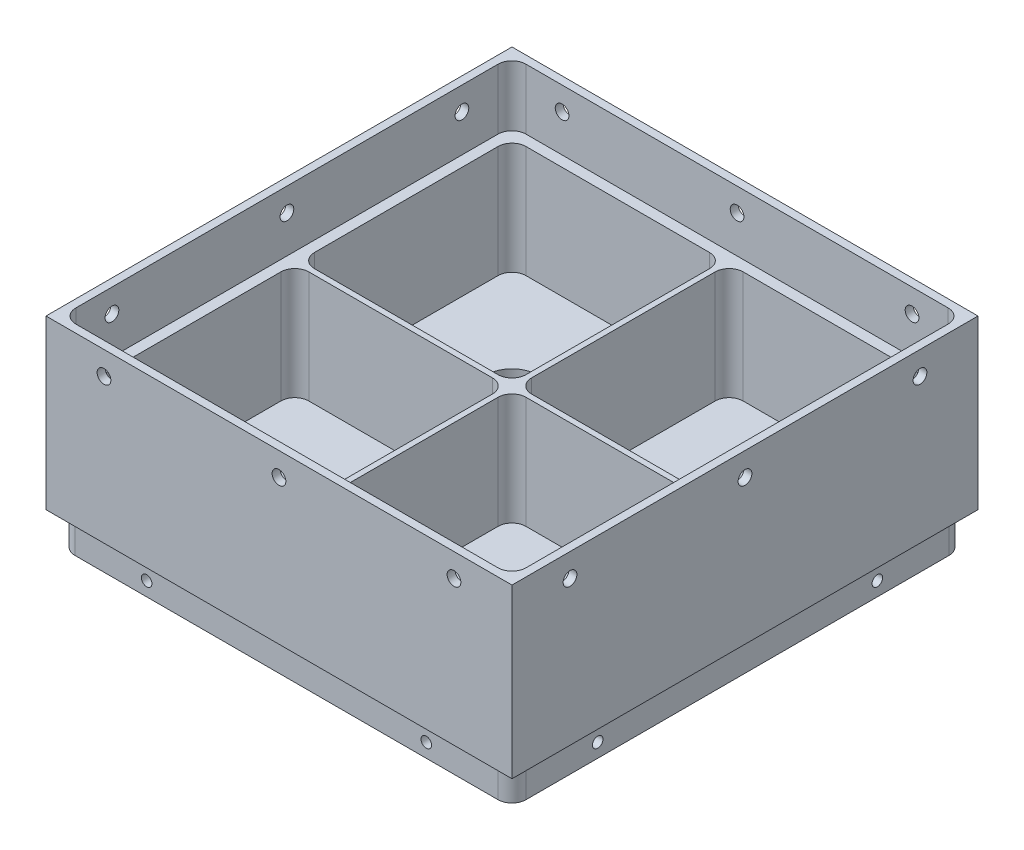
SolidWorks part; units mm, degrees
material "6061-T6 (SS)"
ref_plane "Front Plane" through (0, 0, 0) normal (0, 0, 1) x (1, 0, 0)
ref_plane "Top Plane" through (0, 0, 0) normal (0, 1, 0) x (1, 0, 0)
ref_plane "Right Plane" through (0, 0, 0) normal (1, 0, 0) x (0, 0, -1)
sketch "Sketch1" plane through (0, 0, 0) normal (0, 1, 0) x (1, 0, 0)
  line L0 (0, -50) -> (0, 50) construction
  line L1 (-50, -50) -> (50, -50)
  line L2 (-50, -50) -> (-50, 50)
  line L3 (-50, 50) -> (50, 50)
  line L4 (50, -50) -> (50, 50)
  line L5 (-50, -50) -> (50, 50) construction
  line L6 (-50, 50) -> (50, -50) construction
  line L7 (-50, 0) -> (50, 0) construction
  line L8 (-46, -46) -> (-46, -0.6)
  line L9 (-46, 46) -> (-0.6, 46)
  line L10 (46, -46) -> (46, -0.6)
  line L11 (-46, -46) -> (-0.6, -46)
  line L12 (0.6, -0.6) -> (0.6, 0.6) construction
  line L13 (-46, -0.6) -> (46, -0.6) construction
  line L14 (-0.6, -0.6) -> (-0.6, 0.6) construction
  line L15 (-46, 0.6) -> (46, 0.6) construction
  line L16 (0.6, 46) -> (46, 46)
  line L17 (-0.6, -50) -> (-0.6, 50) construction
  line L18 (0.6, -50) -> (0.6, 50) construction
  line L19 (-46, 0.6) -> (-46, 46)
  line L20 (-46, 46) -> (46, 46) construction
  line L21 (-50, -0.6) -> (50, -0.6) construction
  line L22 (0.6, -46) -> (46, -46)
  line L23 (-46, -46) -> (-46, 46) construction
  line L24 (-50, 0.6) -> (50, 0.6) construction
  line L25 (46, 0.6) -> (46, 46)
  line L26 (-46, -46) -> (46, -46) construction
  line L27 (-0.6, 0.6) -> (-0.6, 46)
  line L28 (46, -46) -> (46, 46) construction
  line L29 (-0.6, -0.6) -> (-0.6, -46)
  line L30 (0.6, 0.6) -> (0.6, 46)
  line L31 (0.6, -0.6) -> (0.6, -46)
  line L32 (-46, 0.6) -> (-0.6, 0.6)
  line L33 (-46, -0.6) -> (-0.6, -0.6)
  line L34 (0.6, 0.6) -> (46, 0.6)
  line L35 (0.6, -0.6) -> (46, -0.6)
  point P0 (0, 0)
  dimension "D1" = 100
  dimension "D2" = 100
  dimension "D3" = 4
  dimension "D4" = 0.6
  dimension "D5" = 0.6
extrude "Boss-Extrude1" add sketch "Sketch1" along normal blind 24
fillet "Fillet1" radius 3 16 edges at (-46, 12, 46) (0.6, 12, 46) (-0.6, 12, 46) (46, 12, 46) (46, 12, -0.6) (46, 12, -46) (0.6, 12, -46) (-0.6, 12, -46) (-46, 12, -0.6) (-46, 12, -46) (0.6, 12, 0.6) (-0.6, 12, 0.6) (0.6, 12, -0.6) (-0.6, 12, -0.6) (46, 12, 0.6) (-46, 12, 0.6)
sketch "Sketch2" plane through (0, 0, 0) normal (0, -1, 0) x (1, 0, 0)
  line L1 (50, -50) -> (-50, -50)
  line L2 (50, -50) -> (50, 50)
  line L3 (50, 50) -> (-50, 50)
  line L4 (-50, -50) -> (-50, 50)
  line L5 (50, -50) -> (-50, 50) construction
  line L6 (50, 50) -> (-50, -50) construction
  point P0 (0, 0)
  dimension "D1" = 100
extrude "Boss-Extrude2" add sketch "Sketch2" along normal blind 6
sketch "Sketch3" plane through (0, -6, 0) normal (0, -1, 0) x (1, 0, 0)
  line L0 (48.4, -48.4) -> (48.4, 48.4)
  line L1 (50, -50) -> (-50, -50)
  line L2 (50, -50) -> (50, 50)
  line L3 (50, 50) -> (-50, 50)
  line L4 (-50, -50) -> (-50, 50)
  line L5 (50, -50) -> (-50, 50) construction
  line L6 (50, 50) -> (-50, -50) construction
  line L7 (48.4, 48.4) -> (-48.4, 48.4)
  line L8 (-48.4, -48.4) -> (-48.4, 48.4)
  line L9 (48.4, -48.4) -> (-48.4, -48.4)
  point P0 (0, 0)
  dimension "D1" = 1.6
extrude "Cut-Extrude1" cut sketch "Sketch3" against normal blind 7
sketch "Sketch4" plane through (0, -6, 0) normal (0, -1, 0) x (1, 0, 0)
  line L1 (47.945, -45.085) -> (-47.945, -45.085) construction
  line L2 (47.945, -45.085) -> (47.945, 45.085) construction
  line L3 (47.945, 45.085) -> (-47.945, 45.085) construction
  line L4 (-47.945, -45.085) -> (-47.945, 45.085) construction
  line L5 (47.945, -45.085) -> (-47.945, 45.085) construction
  line L6 (47.945, 45.085) -> (-47.945, -45.085) construction
  circle A0 centre (42.865, -40.005) radius 1.1305
  circle A1 centre (-42.865, -37.465) radius 1.1305
  circle A2 centre (42.865, 40.005) radius 1.1305
  circle A3 centre (-42.865, 36.195) radius 1.1305
  point P0 (0, 0)
  dimension "D5" = 2.261
  dimension "D8" = 2.261
  dimension "D11" = 2.261
  dimension "D13" = 2.261
  dimension "D1" = 90.17
  dimension "D2" = 95.89
  dimension "D3" = 5.08
  dimension "D4" = 5.08
  dimension "D6" = 90.81
  dimension "D7" = 7.62
  dimension "D9" = 81.28
  dimension "D10" = 90.81
  dimension "D12" = 5.08
  dimension "D14" = 5.08
extrude "Cut-Extrude2" cut sketch "Sketch4" against normal blind 4.7
sketch "Sketch5" plane through (0, 24, 0) normal (0, 1, 0) x (1, 0, 0)
  line L0 (-48.3, -48.3) -> (-48.3, 48.3)
  line L1 (50, -50) -> (-50, -50)
  line L2 (50, -50) -> (50, 50)
  line L3 (50, 50) -> (-50, 50)
  line L4 (-50, -50) -> (-50, 50)
  line L5 (50, -50) -> (-50, 50) construction
  line L6 (50, 50) -> (-50, -50) construction
  line L7 (48.3, 48.3) -> (-48.3, 48.3)
  line L8 (48.3, -48.3) -> (48.3, 48.3)
  line L9 (48.3, -48.3) -> (-48.3, -48.3)
  point P0 (0, 0)
  dimension "D1" = 1.7
extrude "Boss-Extrude3" add sketch "Sketch5" along normal blind 13
fillet "Fillet2" radius 3 8 edges at (48.3, 30.5, 48.3) (-48.3, 30.5, 48.3) (-48.3, 30.5, -48.3) (48.3, 30.5, -48.3) (-48.4, -2.5, -48.4) (-48.4, -2.5, 48.4) (48.4, -2.5, 48.4) (48.4, -2.5, -48.4)
sketch "Sketch6" plane through (0, 0, 0) normal (0, 1, 0) x (1, 0, 0)
  line L0 (-23.3, 46) -> (-23.3, -46) construction
  line L1 (-3.6, 46) -> (-43, 46) construction
  line L2 (-43, -46) -> (-3.6, -46) construction
  line L3 (23.3, -46) -> (23.3, 46) construction
  line L6 (45.8197, 23.4167) -> (46, 23.3)
  line L7 (3.6, -46) -> (43, -46) construction
  line L8 (43, 46) -> (3.6, 46) construction
  line L9 (46, 3.6) -> (46, 43) construction
  line L10 (46, 23.3) -> (-46, 23.3) construction
  line L11 (-46, 43) -> (-46, 3.6) construction
  line L12 (-46, -23.3) -> (46, -23.3) construction
  line L13 (-46, -3.6) -> (-46, -43) construction
  line L14 (46, -43) -> (46, -3.6) construction
  line L15 (23.3, 46) -> (23.3024, 46.2686)
  circle A0 centre (-23.3, 23.3) radius 5.5
  circle A1 centre (23.3, 23.3) radius 5.5
  circle A2 centre (23.3, -23.3) radius 5.5
  circle A3 centre (-23.3, -23.3) radius 5.5
  dimension "D1" = 11
  dimension "D2" = 11
  dimension "D3" = 11
  dimension "D4" = 11
extrude "Cut-Extrude3" cut sketch "Sketch6" against normal through all contours A3 | A2 | A1 | A0
hole_wizard "#32 (0.116) Diameter Hole1" positions "Sketch8" profile "Sketch7" hole size "#32" standard "ANSI Inch" end condition through all
sketch "Sketch8" plane through (0, 0, 50) normal (0, 0, 1) x (1, 0, 0)
  line L0 (0, 37) -> (0, 1) construction
  line L1 (-50, 37) -> (50, 37) construction
  line L2 (50, 1) -> (-50, 1) construction
  point P0 (0, 32)
  point P15 (-37.55, 32)
  point P17 (37.55, 32)
  dimension "D1" = 5
  dimension "D2" = 5
  dimension "D3" = 5
  dimension "D4" = 37.55
  dimension "D5" = 37.55
sketch "Sketch7" plane through (0, 32, 50) normal (1, 0, 0) x (0, -1, 0)
  line L0 (0, 0) -> (0, 100)
  line L1 (0, 100) -> (1.4732, 100)
  line L2 (1.4732, 100) -> (1.4732, 0)
  line L5 (1.4732, 0) -> (0, 0)
  line L11 (0, -6.35) -> (0, 107.95) construction
  dimension "Thru Hole Dia." = 2.9464
  dimension "Thru Hole Depth" = 100
hole_wizard "#32 (0.116) Diameter Hole2" positions "Sketch10" profile "Sketch9" hole size "#32" standard "ANSI Inch" end condition through all
sketch "Sketch10" plane through (50, 0, 0) normal (1, 0, 0) x (0, 0, -1)
  line L0 (-50, 37) -> (50, 37) construction
  line L1 (0, 37) -> (0, 1) construction
  line L2 (50, 1) -> (-50, 1) construction
  line L3 (0, 1) -> (0.0023, 1.0234)
  point P0 (0, 32)
  point P2 (-37.55, 32)
  point P4 (37.55, 32)
  dimension "D1" = 5
  dimension "D2" = 5
  dimension "D3" = 5
  dimension "D4" = 37.55
  dimension "D5" = 37.55
sketch "Sketch9" plane through (50, 32, 0) normal (0, 1, 0) x (0, 0, -1)
  line L0 (0, 0) -> (0, 100)
  line L1 (0, 100) -> (1.4732, 100)
  line L2 (1.4732, 100) -> (1.4732, 0)
  line L5 (1.4732, 0) -> (0, 0)
  line L11 (0, -6.35) -> (0, 107.95) construction
  dimension "Thru Hole Dia." = 2.9464
  dimension "Thru Hole Depth" = 100
hole_wizard "#4-40 Tapped Hole1" positions "Sketch12" profile "Sketch11" tap size "#4-40" standard "ANSI Inch"
sketch "Sketch12" plane through (0, 0, -48.4) normal (0, 0, -1) x (-1, 0, 0)
  line L0 (45.4, 1) -> (-45.4, 1) construction
  line L3 (0, -6) -> (0, 1) construction
  line L4 (45.4, -6) -> (-45.4, -6) construction
  point P0 (-30, -3)
  point P2 (30, -3)
  dimension "D1" = 4
  dimension "D2" = 4
  dimension "D3" = 30
  dimension "D4" = 30
sketch "Sketch11" plane through (30, -3, -48.4) normal (1, 0, 0) x (0, 1, 0)
  line L0 (0, 0) -> (0, 9.5392)
  line L1 (0, 9.5392) -> (1.1303, 8.86)
  line L2 (1.1303, 8.86) -> (1.1303, 0)
  line L5 (1.1303, 0) -> (0, 0)
  line L10 (0, 9.5392) -> (-1.1303, 8.86) construction
  line L11 (0, -6.35) -> (0, 107.95) construction
  dimension "Tap Drill Dia." = 2.2606
  dimension "Tap Drill Depth" = 8.86
  dimension "Drill Angle" = 118
hole_wizard "#4-40 Tapped Hole2" positions "Sketch14" profile "Sketch13" tap size "#4-40" standard "ANSI Inch"
sketch "Sketch14" plane through (48.4, 0, 0) normal (1, 0, 0) x (0, 0, -1)
  line L0 (45.4, 1) -> (-45.4, 1) construction
  line L1 (50, 37) -> (50, 1) construction
  line L2 (-50, 37) -> (-50, 1) construction
  point P0 (-30, -3)
  point P2 (30, -3)
  dimension "D1" = 4
  dimension "D2" = 4
  dimension "D3" = 20
  dimension "D4" = 20
sketch "Sketch13" plane through (48.4, -3, 30) normal (0, 1, 0) x (0, 0, -1)
  line L0 (0, 0) -> (0, 9.5492)
  line L1 (0, 9.5492) -> (1.1303, 8.87)
  line L2 (1.1303, 8.87) -> (1.1303, 0)
  line L5 (1.1303, 0) -> (0, 0)
  line L10 (0, 9.5492) -> (-1.1303, 8.87) construction
  line L11 (0, -6.35) -> (0, 107.95) construction
  dimension "Tap Drill Dia." = 2.2606
  dimension "Tap Drill Depth" = 8.87
  dimension "Drill Angle" = 118
hole_wizard "#4-40 Tapped Hole3" positions "Sketch16" profile "Sketch15" tap size "#4-40" standard "ANSI Inch"
sketch "Sketch16" plane through (0, 0, 48.4) normal (0, 0, 1) x (1, 0, 0)
  line L0 (45.4, 1) -> (-45.4, 1) construction
  line L1 (-50, 37) -> (-50, 1) construction
  line L2 (50, 37) -> (50, 1) construction
  point P0 (-30, -3)
  point P2 (30, -3)
  dimension "D1" = 4
  dimension "D2" = 20
  dimension "D3" = 4
  dimension "D4" = 20
sketch "Sketch15" plane through (-30, -3, 48.4) normal (1, 0, 0) x (0, -1, 0)
  line L0 (0, 0) -> (0, 9.5492)
  line L1 (0, 9.5492) -> (1.1303, 8.87)
  line L2 (1.1303, 8.87) -> (1.1303, 0)
  line L5 (1.1303, 0) -> (0, 0)
  line L10 (0, 9.5492) -> (-1.1303, 8.87) construction
  line L11 (0, -6.35) -> (0, 107.95) construction
  dimension "Tap Drill Dia." = 2.2606
  dimension "Tap Drill Depth" = 8.87
  dimension "Drill Angle" = 118
hole_wizard "#4-40 Tapped Hole4" positions "Sketch18" profile "Sketch17" tap size "#4-40" standard "ANSI Inch"
sketch "Sketch18" plane through (-48.4, 0, 0) normal (-1, 0, 0) x (0, 0, 1)
  line L0 (45.4, 1) -> (-45.4, 1) construction
  line L1 (-50, 37) -> (-50, 1) construction
  line L2 (50, 37) -> (50, 1) construction
  point P0 (-30, -3)
  point P2 (30, -3)
  dimension "D1" = 4
  dimension "D2" = 20
  dimension "D3" = 20
  dimension "D4" = 4
sketch "Sketch17" plane through (-48.4, -3, -30) normal (0, 1, 0) x (0, 0, 1)
  line L0 (0, 0) -> (0, 9.5492)
  line L1 (0, 9.5492) -> (1.1303, 8.87)
  line L2 (1.1303, 8.87) -> (1.1303, 0)
  line L5 (1.1303, 0) -> (0, 0)
  line L10 (0, 9.5492) -> (-1.1303, 8.87) construction
  line L11 (0, -6.35) -> (0, 107.95) construction
  dimension "Tap Drill Dia." = 2.2606
  dimension "Tap Drill Depth" = 8.87
  dimension "Drill Angle" = 118
